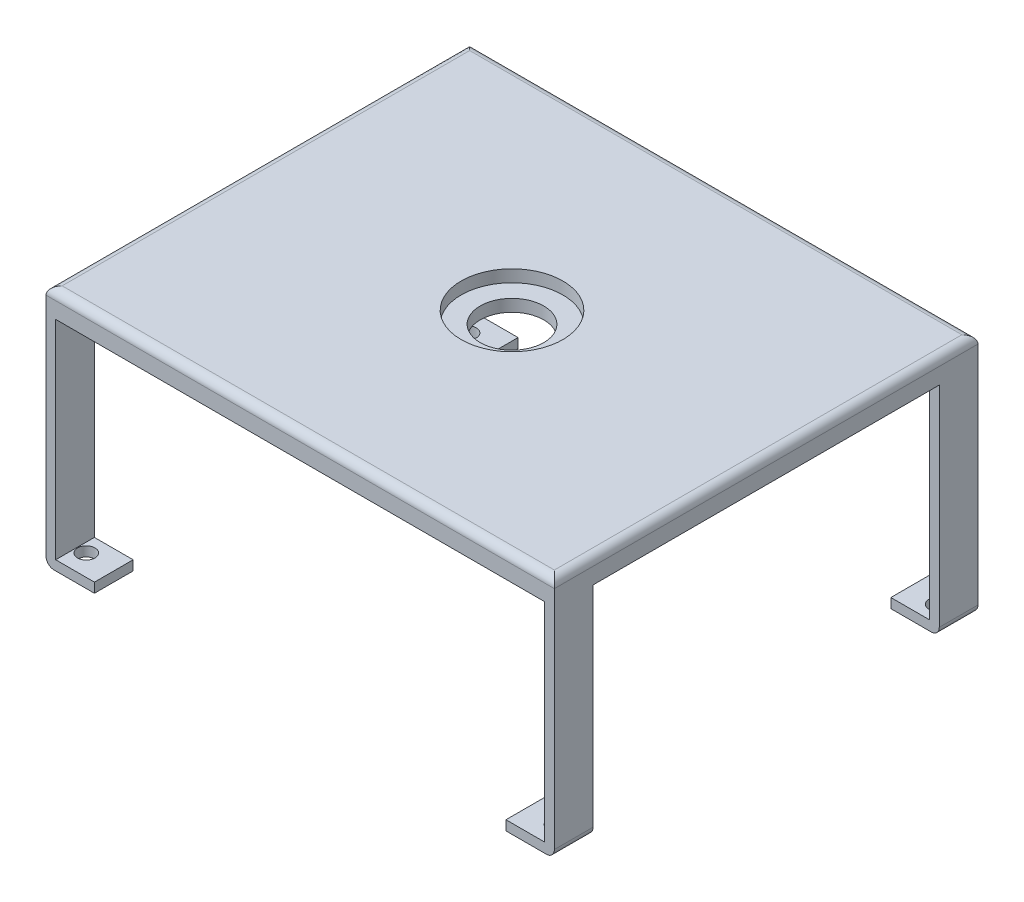
SolidWorks part; units mm, degrees
ref_plane "Plan de face" through (0, 0, 0) normal (0, 0, 1) x (1, 0, 0)
ref_plane "Plan de dessus" through (0, 0, 0) normal (0, 1, 0) x (1, 0, 0)
ref_plane "Plan de droite" through (0, 0, 0) normal (1, 0, 0) x (0, 0, -1)
sketch "Esquisse2" plane through (0, 0, 0) normal (0, 0, 1) x (1, 0, 0)
  line L0 (-64.77, 0) -> (-80.01, 0)
  line L1 (-80.01, 0) -> (-80.01, 76.2)
  line L2 (-80.01, 76.2) -> (80.01, 76.2)
  line L3 (80.01, 76.2) -> (80.01, 0)
  line L4 (80.01, 0) -> (64.77, 0)
  line L5 (64.77, 0) -> (64.77, 3.048)
  line L6 (64.77, 3.048) -> (76.962, 3.048)
  line L7 (76.962, 3.048) -> (76.962, 68.58)
  line L8 (76.962, 68.58) -> (-76.962, 68.58)
  line L9 (-76.962, 68.58) -> (-76.962, 3.048)
  line L10 (-76.962, 3.048) -> (-64.77, 3.048)
  line L11 (-64.77, 3.048) -> (-64.77, 0)
  point P12 (0, 76.2)
  dimension "D1" = 160.02
  dimension "D2" = 76.2
  dimension "D3" = 7.62
  dimension "D4" = 3.048
  dimension "D5" = 3.048
  dimension "D6" = 15.24
extrude "Boss.-Extru.1" add sketch "Esquisse2" along normal blind 133.35
sketch "Esquisse3" plane through (-80.01, 0, 0) normal (-1, 0, 0) x (0, 0, 1)
  line L0 (133.35, 0) -> (0, 0) construction
  line L1 (12.192, 0) -> (121.158, 0)
  line L2 (12.192, 0) -> (12.192, 68.58)
  line L3 (12.192, 68.58) -> (121.158, 68.58)
  line L4 (121.158, 0) -> (121.158, 68.58)
  line L5 (133.35, 76.2) -> (0, 76.2) construction
  line L6 (0, 76.2) -> (0, 0) construction
  line L7 (133.35, 76.2) -> (133.35, 0) construction
  dimension "D1" = 7.62
  dimension "D2" = 12.192
  dimension "D3" = 12.192
extrude "Enlèv. mat.-Extru.1" cut sketch "Esquisse3" against normal through all
sketch "Esquisse4" plane through (0, 3.048, 0) normal (0, 1, 0) x (1, 0, 0)
  line L0 (80.01, -133.35) -> (80.01, 0) construction
  line L2 (80.01, 0) -> (-80.01, 0) construction
  circle A0 centre (73.914, -6.731) radius 2.54
  dimension "D1" = 5.08
  dimension "D2" = 6.096
  dimension "D3" = 6.731
fillet "Congé1" radius 2.54 4 edges at (-80.01, 0, 127.254) (-80.01, 0, 6.096) (80.01, 0, 127.254) (80.01, 0, 6.096)
fillet "Congé2" radius 2.54 4 edges at (80.01, 76.2, 66.675) (0, 76.2, 133.35) (-80.01, 76.2, 66.675) (0, 76.2, 0)
sketch "Esquisse6" plane through (0, 76.2, 0) normal (0, 1, 0) x (1, 0, 0)
  line L0 (-80.01, 0) -> (80.01, 0) construction
  line L1 (-80.01, -133.35) -> (-80.01, 0) construction
  circle A0 centre (0, -66.675) radius 10
  dimension "D1" = 20
  dimension "D2" = 66.675
  dimension "D3" = 80.01
extrude "Enlèv. mat.-Extru.4" cut sketch "Esquisse6" against normal through all
sketch "Esquisse7" plane through (0, 3.048, 0) normal (0, 1, 0) x (1, 0, 0)
  line L2 (-80.01, -133.35) -> (-80.01, 0) construction
  line L3 (80.01, -133.35) -> (-80.01, -133.35) construction
  circle A0 centre (-73.406, -126.746) radius 2.159
  dimension "D1" = 4.318
  dimension "D2" = 6.604
  dimension "D3" = 6.604
sketch "Esquisse8" plane through (0, 3.048, 0) normal (0, 1, 0) x (1, 0, 0)
  line L0 (-80.01, 0) -> (80.01, 0) construction
  line L1 (-80.01, -133.35) -> (-80.01, 0) construction
  circle A0 centre (-73.406, -6.604) radius 2.159
  dimension "D1" = 4.318
  dimension "D2" = 6.604
  dimension "D3" = 6.604
sketch "Esquisse9" plane through (0, 76.2, 0) normal (0, 1, 0) x (1, 0, 0)
  circle A0 centre (0, -66.675) radius 16
  dimension "D1" = 32
extrude "Enlèv. mat.-Extru.5" cut sketch "Esquisse9" against normal blind 3.81
sketch "Sketch1" plane through (0, 0, 0) normal (0, -1, 0) x (1, 0, 0)
  line L0 (-74, 126.675) -> (-74, 6.675) construction
  line L1 (-74, 6.675) -> (74, 6.675) construction
  line L2 (74, 6.675) -> (74, 126.675) construction
  line L3 (74, 126.675) -> (-74, 126.675) construction
  line L4 (-10, 66.675) -> (10, 66.675) construction
  circle A0 centre (74, 126.675) radius 2.75
  circle A1 centre (74, 6.675) radius 2.75
  circle A2 centre (-74, 6.675) radius 2.75
  circle A3 centre (-74, 126.675) radius 2.75
  circle A4 centre (0, 66.675) radius 10 construction
  point P8 (0, 126.675)
  point P15 (-74, 66.675)
  dimension "D3" = 5.5
  dimension "D1" = 120
  dimension "D2" = 148
extrude "Cut-Extrude1" cut sketch "Sketch1" against normal up to surface (3.048 mm away) up to face at (-70.866, 3.048, 127.254)
